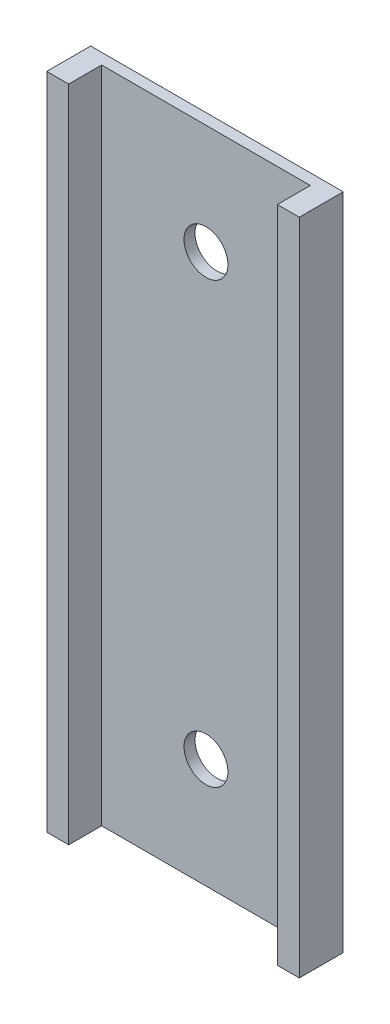
SolidWorks part; units mm, degrees
ref_plane "Front Plane" through (0, 0, 0) normal (0, 0, 1) x (1, 0, 0)
ref_plane "Top Plane" through (0, 0, 0) normal (0, 1, 0) x (1, 0, 0)
ref_plane "Right Plane" through (0, 0, 0) normal (1, 0, 0) x (0, 0, -1)
sketch "Sketch1" plane through (0, 0, 0) normal (0, 0, 1) x (1, 0, 0)
  line L1 (0.0511, -100.03) -> (23.0511, -100.03)
  line L2 (0.0511, -100.03) -> (0.0511, -40.03)
  line L3 (0.0511, -40.03) -> (23.0511, -40.03)
  line L4 (23.0511, -100.03) -> (23.0511, -40.03)
  dimension "D1" = 23
  dimension "D2" = 60
extrude "Boss-Extrude1" add sketch "Sketch1" along normal blind 4
sketch "Sketch2" plane through (0, -40.03, 0) normal (0, 1, 0) x (1, 0, 0)
  line L1 (0.0511, -4) -> (0.0511, 0) construction
  line L2 (21.0511, -1) -> (2.0511, -1)
  line L3 (21.0511, -1) -> (21.0511, -4.6526)
  line L4 (21.0511, -4.6526) -> (2.0511, -4.6526)
  line L8 (2.0511, -1) -> (2.0511, -4.6526)
  line L9 (23.0511, -4) -> (23.0511, 0) construction
  line L10 (23.0511, 0) -> (0.0511, 0) construction
  point P4 (2.0511, -2.8263)
  point P7 (21.0511, -2.8263)
  dimension "D1" = 2
  dimension "D2" = 2
  dimension "D3" = 1
extrude "Cut-Extrude1" cut sketch "Sketch2" against normal through all
sketch "Sketch4" plane through (0, 0, 0) normal (0, 0, -1) x (-1, 0, 0)
  line L0 (-23.0511, -100.03) -> (-23.0511, -40.03) construction
  line L1 (-0.0511, -100.03) -> (-23.0511, -100.03) construction
  line L2 (-23.0511, -40.03) -> (-0.0511, -40.03) construction
  circle A0 centre (-11.5511, -50.03) radius 2
  circle A1 centre (-11.5511, -90.03) radius 2
  dimension "D5" = 4
  dimension "D6" = 4
  dimension "D1" = 11.5
  dimension "D2" = 11.5
  dimension "D3" = 10
  dimension "D4" = 10
extrude "Cut-Extrude2" cut sketch "Sketch4" against normal through all
